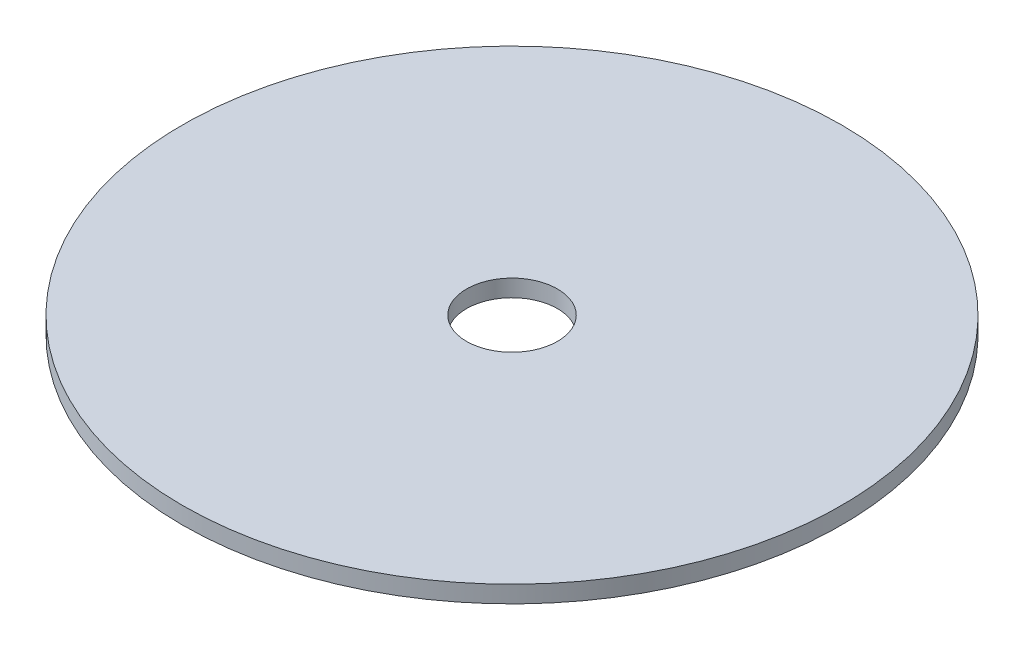
SolidWorks part; units mm, degrees
ref_plane "Front Plane" through (0, 0, 0) normal (0, 0, 1) x (1, 0, 0)
ref_plane "Top Plane" through (0, 0, 0) normal (0, 1, 0) x (1, 0, 0)
ref_plane "Right Plane" through (0, 0, 0) normal (1, 0, 0) x (0, 0, -1)
sketch "Sketch1" plane through (0, 0, 0) normal (0, 1, 0) x (1, 0, 0)
  circle A0 centre (0, 0) radius 58
  circle A1 centre (0, 0) radius 8
  dimension "D1" = 116
  dimension "D2" = 16
extrude "Boss-Extrude1" add sketch "Sketch1" along normal mid plane 3
